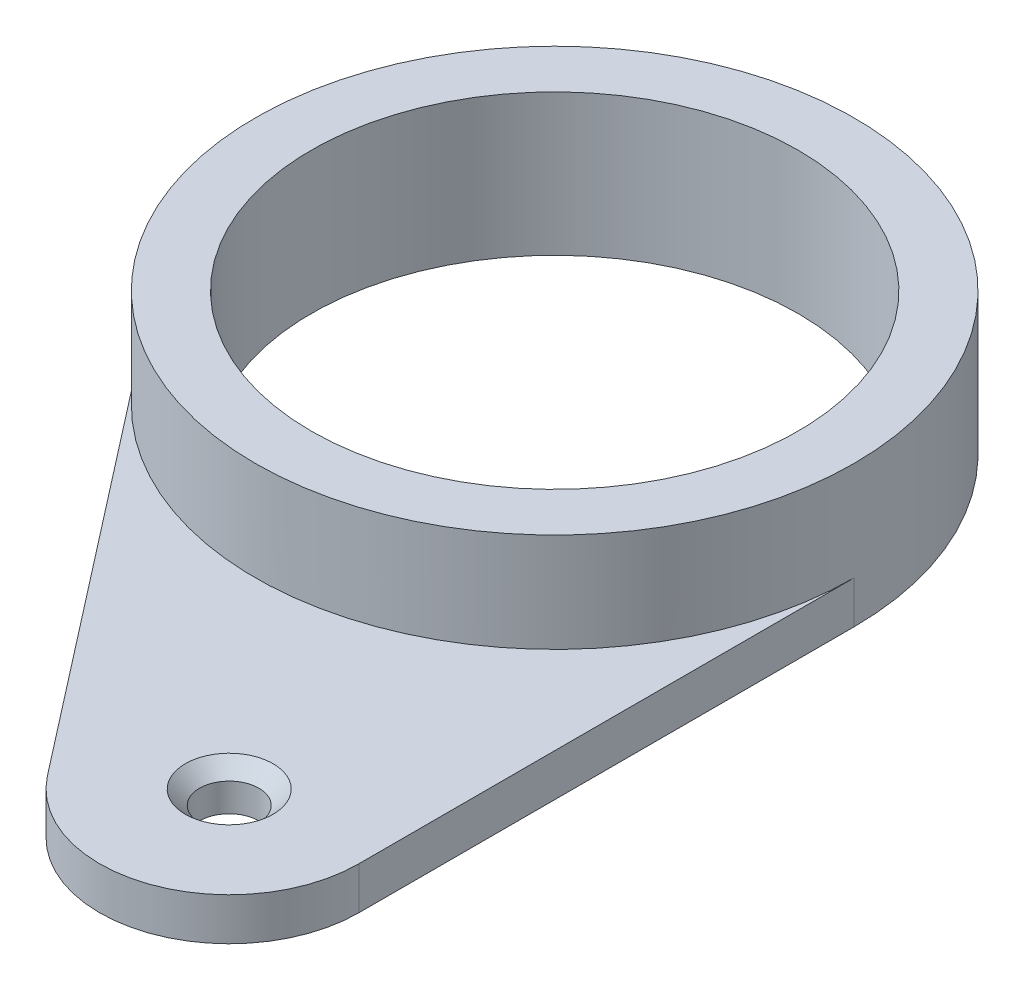
SolidWorks part; units mm, degrees
ref_plane "Front Plane" through (0, 0, 0) normal (0, 0, 1) x (1, 0, 0)
ref_plane "Top Plane" through (0, 0, 0) normal (0, 1, 0) x (1, 0, 0)
ref_plane "Right Plane" through (0, 0, 0) normal (1, 0, 0) x (0, 0, -1)
sketch "Sketch1" plane through (0, 0, 0) normal (0, 1, 0) x (1, 0, 0)
  line L0 (-7.2318, -5.6137) -> (-29.2271, 22.7215)
  line L1 (9.155, 0) -> (9.155, 35)
  line L2 (-26.0064, 25.017) -> (-29.2271, 22.7215) construction
  line L3 (5.2, 35) -> (9.155, 35) construction
  circle A0 centre (0, 0) radius 2.1
  arc A1 (9.155, 0) -> (-7.2318, -5.6137) centre (0, 0) cw
  circle A2 centre (-12, 35) radius 17.2
  arc A3 (-29.2271, 22.7215) -> (9.155, 35) centre (-12, 35) cw
  dimension "D1" = 34.4
  dimension "D2" = 4.2
  dimension "D3" = 35
  dimension "D4" = 12
extrude "Boss-Extrude1" add sketch "Sketch1" along normal blind 3 contours A3 L0 A1 L1 A2 A0
chamfer "Chamfer1" distance 1 angle 45 1 edges at (0, 3, 2.1)
sketch "Sketch2" plane through (0, 3, 0) normal (0, 1, 0) x (1, 0, 0)
  circle A0 centre (-12, 35) radius 17.2
  circle A1 centre (-12, 35) radius 21.155
extrude "Boss-Extrude2" add sketch "Sketch2" along normal blind 7
